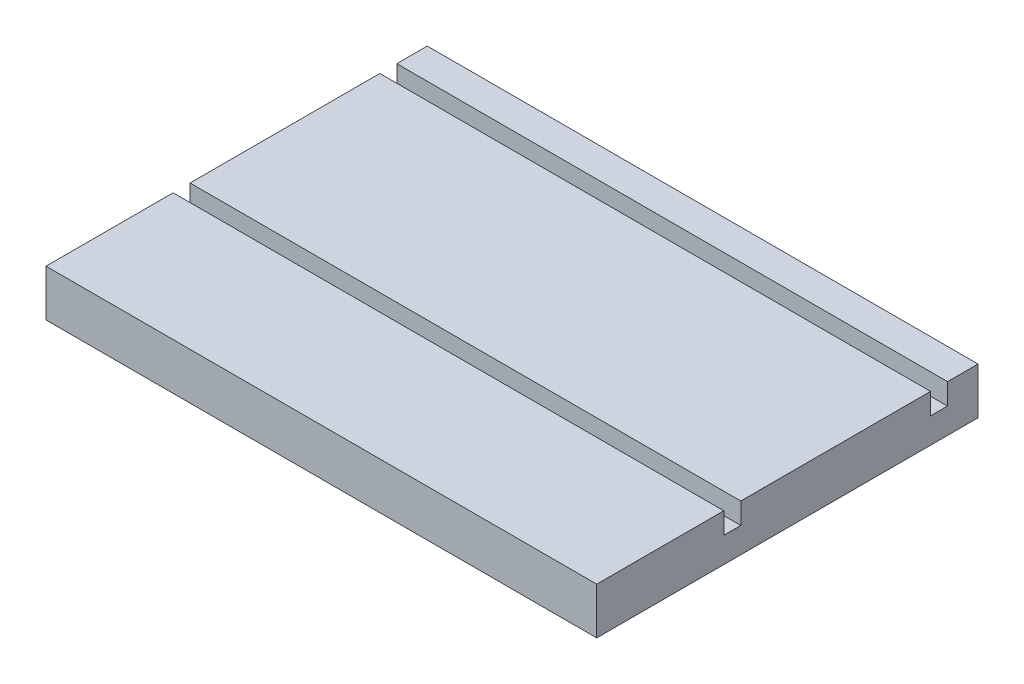
SolidWorks part; units mm, degrees
ref_plane "Front Plane" through (0, 0, 0) normal (0, 0, 1) x (1, 0, 0)
ref_plane "Top Plane" through (0, 0, 0) normal (0, 1, 0) x (1, 0, 0)
ref_plane "Right Plane" through (0, 0, 0) normal (1, 0, 0) x (0, 0, -1)
sketch "Sketch1" plane through (0, 0, 0) normal (0, 1, 0) x (1, 0, 0)
  line L1 (0, 0) -> (650, 0)
  line L2 (0, 0) -> (0, 450)
  line L3 (0, 450) -> (650, 450)
  line L4 (650, 0) -> (650, 450)
  dimension "D1" = 650
  dimension "D2" = 450
extrude "Boss-Extrude1" add sketch "Sketch1" along normal blind 55
sketch "Sketch2" plane through (650, 0, 0) normal (1, 0, 0) x (0, 0, -1)
  line L0 (0, 55) -> (450, 55) construction
  line L1 (394, 55) -> (414, 55)
  line L2 (394, 55) -> (394, 30)
  line L3 (394, 30) -> (414, 30)
  line L4 (414, 55) -> (414, 30)
  line L5 (450, 55) -> (450, 0) construction
  line L7 (150, 55) -> (170, 55)
  line L8 (150, 55) -> (150, 30)
  line L9 (150, 30) -> (170, 30)
  line L10 (170, 55) -> (170, 30)
  dimension "D1" = 25
  dimension "D2" = 20
  dimension "D3" = 36
  dimension "D4" = 280
  dimension "D5" = 20
  dimension "D6" = 25
extrude "Cut-Extrude1" cut sketch "Sketch2" against normal through all
